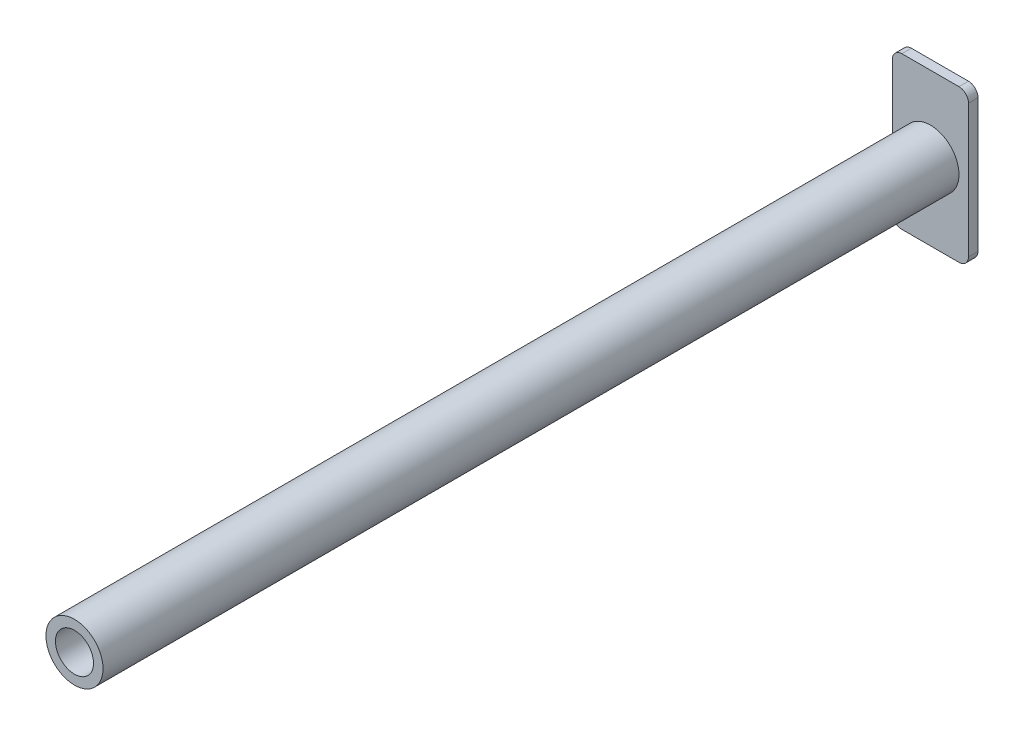
SolidWorks part; units mm, degrees
ref_plane "Front Plane" through (0, 0, 0) normal (0, 0, 1) x (1, 0, 0)
ref_plane "Top Plane" through (0, 0, 0) normal (0, 1, 0) x (1, 0, 0)
ref_plane "Right Plane" through (0, 0, 0) normal (1, 0, 0) x (0, 0, -1)
sketch "Plate Sketch" plane through (0, 0, 0) normal (0, 0, 1) x (1, 0, 0)
  line L0 (0, 101) -> (0, -101) construction
  line L1 (-40, 80) -> (40, 80)
  line L2 (-40, 80) -> (-40, -80)
  line L3 (-40, -80) -> (40, -80)
  line L4 (40, 80) -> (40, -80)
  line L5 (-40, 80) -> (40, -80) construction
  line L6 (-40, -80) -> (40, 80) construction
  point P0 (0, 0)
  point P9 (0, 0)
  dimension "D1" = 80
  dimension "D2" = 160
  dimension "D3" = 202
extrude "Plate Extrude" add sketch "Plate Sketch" along normal blind 10
fillet "Plate Fillet" radius 10 4 edges at (40, -80, 5) (-40, -80, 5) (-40, 80, 5) (40, 80, 5)
sketch "Pole Sketch" plane through (0, 0, 10) normal (0, 0, 1) x (1, 0, 0)
  circle A0 centre (0, 0) radius 30
  circle A1 centre (0, 0) radius 20
  dimension "D1" = 10
  dimension "D2" = 60
extrude "Pole Extrude" add sketch "Pole Sketch" along normal blind 900
